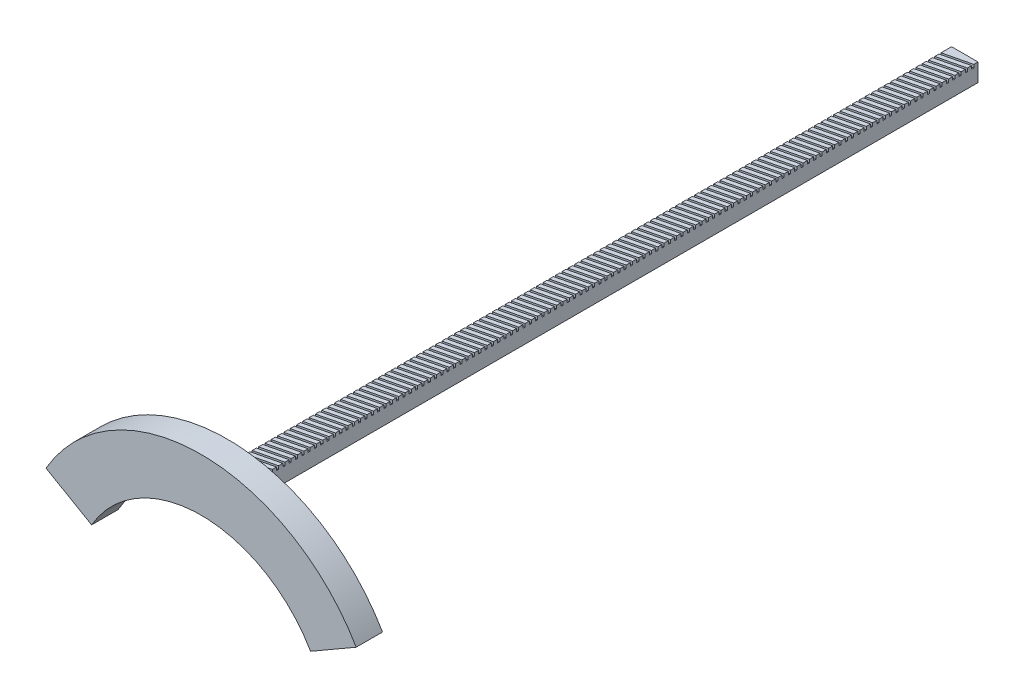
SolidWorks part; units mm, degrees
ref_plane "Ön Düzlem" through (0, 0, 0) normal (0, 0, 1) x (1, 0, 0)
ref_plane "Üst Düzlem" through (0, 0, 0) normal (0, 1, 0) x (1, 0, 0)
ref_plane "Sağ Düzlem" through (0, 0, 0) normal (1, 0, 0) x (0, 0, -1)
sketch "Sketch1" plane through (0, 0, 0) normal (0, 0, 1) x (1, 0, 0)
  line L0 (0, 0) -> (-0.6272, 5.9671) construction
  line L1 (-0.6272, 5.9671) -> (0.6272, 5.9671) construction
  line L2 (0.6272, 5.9671) -> (0, 0) construction
  line L3 (-0.6272, 5.9671) -> (-0.6272, 6.9671)
  line L4 (-0.6272, 6.9671) -> (0.6272, 6.9671)
  line L5 (0.6272, 6.9671) -> (0.6272, 5.9671)
  circle A0 centre (0, 0) radius 6 construction
  arc A1 (-0.6272, 5.9671) -> (0.6272, 5.9671) centre (0, 0) cw
  dimension "D1" = 12
  dimension "D2" = 12
  dimension "D3" = 1
extrude "Boss-Extrude1" add sketch "Sketch1" along normal blind 35 contours L3 A1 L5 L4
sketch "Sketch2" plane through (0, 0, 35) normal (0, 0, 1) x (1, 0, 0)
  line L1 (0, 8.5) -> (0, 0) construction
  line L2 (0, 0) -> (-7.3612, 4.25) construction
  line L3 (-7.3612, 4.25) -> (-5.1962, 3)
  line L4 (0, 8.5) -> (0, 6)
  arc A0 (0, 8.5) -> (-7.3612, 4.25) centre (0, 0) ccw
  arc A1 (-5.1962, 3) -> (0, 6) centre (0, 0) cw
  dimension "D1" = 60
  dimension "D2" = 2.5
  dimension "D3" = 6
extrude "Boss-Extrude2" add sketch "Sketch2" along normal blind 1.25
mirror "Mirror1" about plane through (0, 8.5, 36.25) normal (-1, 0, 0) of "Boss-Extrude2"
sketch "Sketch3" plane through (0, 6.9671, 0) normal (0, 1, 0) x (1, 0, 0)
  line L0 (0.6272, -0.2) -> (-0.6272, -0.5)
  line L1 (0.6272, -35) -> (0.6272, 0) construction
  line L2 (-0.6272, -35) -> (-0.6272, 0) construction
  line L3 (-0.6272, -0.5) -> (-0.6272, -0.6)
  line L4 (-0.6272, -0.6) -> (0.6272, -0.3)
  line L5 (0.6272, -0.3) -> (0.6272, -0.2)
  line L278 (-0.6272, -0.8) -> (-0.6272, -0.9)
  line L279 (-0.6272, -0.9) -> (0.6272, -0.6)
  line L280 (0.6272, -0.5) -> (-0.6272, -0.8)
  line L281 (0.6272, -0.6) -> (0.6272, -0.5)
  line L282 (-0.6272, -1.1) -> (-0.6272, -1.2)
  line L283 (-0.6272, -1.2) -> (0.6272, -0.9)
  line L284 (0.6272, -0.8) -> (-0.6272, -1.1)
  line L285 (0.6272, -0.9) -> (0.6272, -0.8)
  line L286 (-0.6272, -1.4) -> (-0.6272, -1.5)
  line L287 (-0.6272, -1.5) -> (0.6272, -1.2)
  line L288 (0.6272, -1.1) -> (-0.6272, -1.4)
  line L289 (0.6272, -1.2) -> (0.6272, -1.1)
  line L290 (-0.6272, -1.7) -> (-0.6272, -1.8)
  line L291 (-0.6272, -1.8) -> (0.6272, -1.5)
  line L292 (0.6272, -1.4) -> (-0.6272, -1.7)
  line L293 (0.6272, -1.5) -> (0.6272, -1.4)
  line L294 (-0.6272, -1.9999) -> (-0.6272, -2.0999)
  line L295 (-0.6272, -2.0999) -> (0.6272, -1.7999)
  line L296 (0.6272, -1.6999) -> (-0.6272, -1.9999)
  line L297 (0.6272, -1.7999) -> (0.6272, -1.6999)
  line L298 (-0.6272, -2.2999) -> (-0.6272, -2.3999)
  line L299 (-0.6272, -2.3999) -> (0.6272, -2.0999)
  line L300 (0.6272, -1.9999) -> (-0.6272, -2.2999)
  line L301 (0.6272, -2.0999) -> (0.6272, -1.9999)
  line L302 (-0.6272, -2.5999) -> (-0.6272, -2.6999)
  line L303 (-0.6272, -2.6999) -> (0.6272, -2.3999)
  line L304 (0.6272, -2.2999) -> (-0.6272, -2.5999)
  line L305 (0.6272, -2.3999) -> (0.6272, -2.2999)
  line L306 (-0.6272, -2.8999) -> (-0.6272, -2.9999)
  line L307 (-0.6272, -2.9999) -> (0.6272, -2.6999)
  line L308 (0.6272, -2.5999) -> (-0.6272, -2.8999)
  line L309 (0.6272, -2.6999) -> (0.6272, -2.5999)
  line L310 (-0.6272, -3.1999) -> (-0.6272, -3.2999)
  line L311 (-0.6272, -3.2999) -> (0.6272, -2.9999)
  line L312 (0.6272, -2.8999) -> (-0.6272, -3.1999)
  line L313 (0.6272, -2.9999) -> (0.6272, -2.8999)
  line L314 (-0.6272, -3.4999) -> (-0.6272, -3.5999)
  line L315 (-0.6272, -3.5999) -> (0.6272, -3.2999)
  line L316 (0.6272, -3.1999) -> (-0.6272, -3.4999)
  line L317 (0.6272, -3.2999) -> (0.6272, -3.1999)
  line L318 (-0.6272, -3.7999) -> (-0.6272, -3.8999)
  line L319 (-0.6272, -3.8999) -> (0.6272, -3.5999)
  line L320 (0.6272, -3.4999) -> (-0.6272, -3.7999)
  line L321 (0.6272, -3.5999) -> (0.6272, -3.4999)
  line L322 (-0.6272, -4.0999) -> (-0.6272, -4.1999)
  line L323 (-0.6272, -4.1999) -> (0.6272, -3.8999)
  line L324 (0.6272, -3.7999) -> (-0.6272, -4.0999)
  line L325 (0.6272, -3.8999) -> (0.6272, -3.7999)
  line L326 (-0.6272, -4.3999) -> (-0.6272, -4.4999)
  line L327 (-0.6272, -4.4999) -> (0.6272, -4.1999)
  line L328 (0.6272, -4.0999) -> (-0.6272, -4.3999)
  line L329 (0.6272, -4.1999) -> (0.6272, -4.0999)
  line L330 (-0.6272, -4.6999) -> (-0.6272, -4.7999)
  line L331 (-0.6272, -4.7999) -> (0.6272, -4.4999)
  line L332 (0.6272, -4.3999) -> (-0.6272, -4.6999)
  line L333 (0.6272, -4.4999) -> (0.6272, -4.3999)
  line L334 (-0.6272, -4.9998) -> (-0.6272, -5.0998)
  line L335 (-0.6272, -5.0998) -> (0.6272, -4.7998)
  line L336 (0.6272, -4.6998) -> (-0.6272, -4.9998)
  line L337 (0.6272, -4.7998) -> (0.6272, -4.6998)
  line L338 (-0.6272, -5.2998) -> (-0.6272, -5.3998)
  line L339 (-0.6272, -5.3998) -> (0.6272, -5.0998)
  line L340 (0.6272, -4.9998) -> (-0.6272, -5.2998)
  line L341 (0.6272, -5.0998) -> (0.6272, -4.9998)
  line L342 (-0.6272, -5.5998) -> (-0.6272, -5.6998)
  line L343 (-0.6272, -5.6998) -> (0.6272, -5.3998)
  line L344 (0.6272, -5.2998) -> (-0.6272, -5.5998)
  line L345 (0.6272, -5.3998) -> (0.6272, -5.2998)
  line L346 (-0.6272, -5.8998) -> (-0.6272, -5.9998)
  line L347 (-0.6272, -5.9998) -> (0.6272, -5.6998)
  line L348 (0.6272, -5.5998) -> (-0.6272, -5.8998)
  line L349 (0.6272, -5.6998) -> (0.6272, -5.5998)
  line L350 (-0.6272, -6.1998) -> (-0.6272, -6.2998)
  line L351 (-0.6272, -6.2998) -> (0.6272, -5.9998)
  line L352 (0.6272, -5.8998) -> (-0.6272, -6.1998)
  line L353 (0.6272, -5.9998) -> (0.6272, -5.8998)
  line L354 (-0.6272, -6.4998) -> (-0.6272, -6.5998)
  line L355 (-0.6272, -6.5998) -> (0.6272, -6.2998)
  line L356 (0.6272, -6.1998) -> (-0.6272, -6.4998)
  line L357 (0.6272, -6.2998) -> (0.6272, -6.1998)
  line L358 (-0.6272, -6.7998) -> (-0.6272, -6.8998)
  line L359 (-0.6272, -6.8998) -> (0.6272, -6.5998)
  line L360 (0.6272, -6.4998) -> (-0.6272, -6.7998)
  line L361 (0.6272, -6.5998) -> (0.6272, -6.4998)
  line L362 (-0.6272, -7.0998) -> (-0.6272, -7.1998)
  line L363 (-0.6272, -7.1998) -> (0.6272, -6.8998)
  line L364 (0.6272, -6.7998) -> (-0.6272, -7.0998)
  line L365 (0.6272, -6.8998) -> (0.6272, -6.7998)
  line L366 (-0.6272, -7.3998) -> (-0.6272, -7.4998)
  line L367 (-0.6272, -7.4998) -> (0.6272, -7.1998)
  line L368 (0.6272, -7.0998) -> (-0.6272, -7.3998)
  line L369 (0.6272, -7.1998) -> (0.6272, -7.0998)
  line L370 (-0.6272, -7.6998) -> (-0.6272, -7.7998)
  line L371 (-0.6272, -7.7998) -> (0.6272, -7.4998)
  line L372 (0.6272, -7.3998) -> (-0.6272, -7.6998)
  line L373 (0.6272, -7.4998) -> (0.6272, -7.3998)
  line L374 (-0.6272, -7.9997) -> (-0.6272, -8.0997)
  line L375 (-0.6272, -8.0997) -> (0.6272, -7.7997)
  line L376 (0.6272, -7.6997) -> (-0.6272, -7.9997)
  line L377 (0.6272, -7.7997) -> (0.6272, -7.6997)
  line L378 (-0.6272, -8.2997) -> (-0.6272, -8.3997)
  line L379 (-0.6272, -8.3997) -> (0.6272, -8.0997)
  line L380 (0.6272, -7.9997) -> (-0.6272, -8.2997)
  line L381 (0.6272, -8.0997) -> (0.6272, -7.9997)
  line L382 (-0.6272, -8.5997) -> (-0.6272, -8.6997)
  line L383 (-0.6272, -8.6997) -> (0.6272, -8.3997)
  line L384 (0.6272, -8.2997) -> (-0.6272, -8.5997)
  line L385 (0.6272, -8.3997) -> (0.6272, -8.2997)
  line L386 (-0.6272, -8.8997) -> (-0.6272, -8.9997)
  line L387 (-0.6272, -8.9997) -> (0.6272, -8.6997)
  line L388 (0.6272, -8.5997) -> (-0.6272, -8.8997)
  line L389 (0.6272, -8.6997) -> (0.6272, -8.5997)
  line L390 (-0.6272, -9.1997) -> (-0.6272, -9.2997)
  line L391 (-0.6272, -9.2997) -> (0.6272, -8.9997)
  line L392 (0.6272, -8.8997) -> (-0.6272, -9.1997)
  line L393 (0.6272, -8.9997) -> (0.6272, -8.8997)
  line L394 (-0.6272, -9.4997) -> (-0.6272, -9.5997)
  line L395 (-0.6272, -9.5997) -> (0.6272, -9.2997)
  line L396 (0.6272, -9.1997) -> (-0.6272, -9.4997)
  line L397 (0.6272, -9.2997) -> (0.6272, -9.1997)
  line L398 (-0.6272, -9.7997) -> (-0.6272, -9.8997)
  line L399 (-0.6272, -9.8997) -> (0.6272, -9.5997)
  line L400 (0.6272, -9.4997) -> (-0.6272, -9.7997)
  line L401 (0.6272, -9.5997) -> (0.6272, -9.4997)
  line L402 (-0.6272, -10.0997) -> (-0.6272, -10.1997)
  line L403 (-0.6272, -10.1997) -> (0.6272, -9.8997)
  line L404 (0.6272, -9.7997) -> (-0.6272, -10.0997)
  line L405 (0.6272, -9.8997) -> (0.6272, -9.7997)
  line L406 (-0.6272, -10.3997) -> (-0.6272, -10.4997)
  line L407 (-0.6272, -10.4997) -> (0.6272, -10.1997)
  line L408 (0.6272, -10.0997) -> (-0.6272, -10.3997)
  line L409 (0.6272, -10.1997) -> (0.6272, -10.0997)
  line L410 (-0.6272, -10.6997) -> (-0.6272, -10.7997)
  line L411 (-0.6272, -10.7997) -> (0.6272, -10.4997)
  line L412 (0.6272, -10.3997) -> (-0.6272, -10.6997)
  line L413 (0.6272, -10.4997) -> (0.6272, -10.3997)
  line L414 (-0.6272, -10.9996) -> (-0.6272, -11.0996)
  line L415 (-0.6272, -11.0996) -> (0.6272, -10.7996)
  line L416 (0.6272, -10.6996) -> (-0.6272, -10.9996)
  line L417 (0.6272, -10.7996) -> (0.6272, -10.6996)
  line L418 (-0.6272, -11.2996) -> (-0.6272, -11.3996)
  line L419 (-0.6272, -11.3996) -> (0.6272, -11.0996)
  line L420 (0.6272, -10.9996) -> (-0.6272, -11.2996)
  line L421 (0.6272, -11.0996) -> (0.6272, -10.9996)
  line L422 (-0.6272, -11.5996) -> (-0.6272, -11.6996)
  line L423 (-0.6272, -11.6996) -> (0.6272, -11.3996)
  line L424 (0.6272, -11.2996) -> (-0.6272, -11.5996)
  line L425 (0.6272, -11.3996) -> (0.6272, -11.2996)
  line L426 (-0.6272, -11.8996) -> (-0.6272, -11.9996)
  line L427 (-0.6272, -11.9996) -> (0.6272, -11.6996)
  line L428 (0.6272, -11.5996) -> (-0.6272, -11.8996)
  line L429 (0.6272, -11.6996) -> (0.6272, -11.5996)
  line L430 (-0.6272, -12.1996) -> (-0.6272, -12.2996)
  line L431 (-0.6272, -12.2996) -> (0.6272, -11.9996)
  line L432 (0.6272, -11.8996) -> (-0.6272, -12.1996)
  line L433 (0.6272, -11.9996) -> (0.6272, -11.8996)
  line L434 (-0.6272, -12.4996) -> (-0.6272, -12.5996)
  line L435 (-0.6272, -12.5996) -> (0.6272, -12.2996)
  line L436 (0.6272, -12.1996) -> (-0.6272, -12.4996)
  line L437 (0.6272, -12.2996) -> (0.6272, -12.1996)
  line L438 (-0.6272, -12.7996) -> (-0.6272, -12.8996)
  line L439 (-0.6272, -12.8996) -> (0.6272, -12.5996)
  line L440 (0.6272, -12.4996) -> (-0.6272, -12.7996)
  line L441 (0.6272, -12.5996) -> (0.6272, -12.4996)
  line L442 (-0.6272, -13.0996) -> (-0.6272, -13.1996)
  line L443 (-0.6272, -13.1996) -> (0.6272, -12.8996)
  line L444 (0.6272, -12.7996) -> (-0.6272, -13.0996)
  line L445 (0.6272, -12.8996) -> (0.6272, -12.7996)
  line L446 (-0.6272, -13.3996) -> (-0.6272, -13.4996)
  line L447 (-0.6272, -13.4996) -> (0.6272, -13.1996)
  line L448 (0.6272, -13.0996) -> (-0.6272, -13.3996)
  line L449 (0.6272, -13.1996) -> (0.6272, -13.0996)
  line L450 (-0.6272, -13.6996) -> (-0.6272, -13.7996)
  line L451 (-0.6272, -13.7996) -> (0.6272, -13.4996)
  line L452 (0.6272, -13.3996) -> (-0.6272, -13.6996)
  line L453 (0.6272, -13.4996) -> (0.6272, -13.3996)
  line L454 (-0.6272, -13.9995) -> (-0.6272, -14.0995)
  line L455 (-0.6272, -14.0995) -> (0.6272, -13.7995)
  line L456 (0.6272, -13.6995) -> (-0.6272, -13.9995)
  line L457 (0.6272, -13.7995) -> (0.6272, -13.6995)
  line L458 (-0.6272, -14.2995) -> (-0.6272, -14.3995)
  line L459 (-0.6272, -14.3995) -> (0.6272, -14.0995)
  line L460 (0.6272, -13.9995) -> (-0.6272, -14.2995)
  line L461 (0.6272, -14.0995) -> (0.6272, -13.9995)
  line L462 (-0.6272, -14.5995) -> (-0.6272, -14.6995)
  line L463 (-0.6272, -14.6995) -> (0.6272, -14.3995)
  line L464 (0.6272, -14.2995) -> (-0.6272, -14.5995)
  line L465 (0.6272, -14.3995) -> (0.6272, -14.2995)
  line L466 (-0.6272, -14.8995) -> (-0.6272, -14.9995)
  line L467 (-0.6272, -14.9995) -> (0.6272, -14.6995)
  line L468 (0.6272, -14.5995) -> (-0.6272, -14.8995)
  line L469 (0.6272, -14.6995) -> (0.6272, -14.5995)
  line L470 (-0.6272, -15.1995) -> (-0.6272, -15.2995)
  line L471 (-0.6272, -15.2995) -> (0.6272, -14.9995)
  line L472 (0.6272, -14.8995) -> (-0.6272, -15.1995)
  line L473 (0.6272, -14.9995) -> (0.6272, -14.8995)
  line L474 (-0.6272, -15.4995) -> (-0.6272, -15.5995)
  line L475 (-0.6272, -15.5995) -> (0.6272, -15.2995)
  line L476 (0.6272, -15.1995) -> (-0.6272, -15.4995)
  line L477 (0.6272, -15.2995) -> (0.6272, -15.1995)
  line L478 (-0.6272, -15.7995) -> (-0.6272, -15.8995)
  line L479 (-0.6272, -15.8995) -> (0.6272, -15.5995)
  line L480 (0.6272, -15.4995) -> (-0.6272, -15.7995)
  line L481 (0.6272, -15.5995) -> (0.6272, -15.4995)
  line L482 (-0.6272, -16.0995) -> (-0.6272, -16.1995)
  line L483 (-0.6272, -16.1995) -> (0.6272, -15.8995)
  line L484 (0.6272, -15.7995) -> (-0.6272, -16.0995)
  line L485 (0.6272, -15.8995) -> (0.6272, -15.7995)
  line L486 (-0.6272, -16.3995) -> (-0.6272, -16.4995)
  line L487 (-0.6272, -16.4995) -> (0.6272, -16.1995)
  line L488 (0.6272, -16.0995) -> (-0.6272, -16.3995)
  line L489 (0.6272, -16.1995) -> (0.6272, -16.0995)
  line L490 (-0.6272, -16.6995) -> (-0.6272, -16.7995)
  line L491 (-0.6272, -16.7995) -> (0.6272, -16.4995)
  line L492 (0.6272, -16.3995) -> (-0.6272, -16.6995)
  line L493 (0.6272, -16.4995) -> (0.6272, -16.3995)
  line L494 (-0.6272, -16.9994) -> (-0.6272, -17.0994)
  line L495 (-0.6272, -17.0994) -> (0.6272, -16.7994)
  line L496 (0.6272, -16.6994) -> (-0.6272, -16.9994)
  line L497 (0.6272, -16.7994) -> (0.6272, -16.6994)
  line L498 (-0.6272, -17.2994) -> (-0.6272, -17.3994)
  line L499 (-0.6272, -17.3994) -> (0.6272, -17.0994)
  line L500 (0.6272, -16.9994) -> (-0.6272, -17.2994)
  line L501 (0.6272, -17.0994) -> (0.6272, -16.9994)
  line L502 (-0.6272, -17.5994) -> (-0.6272, -17.6994)
  line L503 (-0.6272, -17.6994) -> (0.6272, -17.3994)
  line L504 (0.6272, -17.2994) -> (-0.6272, -17.5994)
  line L505 (0.6272, -17.3994) -> (0.6272, -17.2994)
  line L506 (-0.6272, -17.8994) -> (-0.6272, -17.9994)
  line L507 (-0.6272, -17.9994) -> (0.6272, -17.6994)
  line L508 (0.6272, -17.5994) -> (-0.6272, -17.8994)
  line L509 (0.6272, -17.6994) -> (0.6272, -17.5994)
  line L510 (-0.6272, -18.1994) -> (-0.6272, -18.2994)
  line L511 (-0.6272, -18.2994) -> (0.6272, -17.9994)
  line L512 (0.6272, -17.8994) -> (-0.6272, -18.1994)
  line L513 (0.6272, -17.9994) -> (0.6272, -17.8994)
  line L514 (-0.6272, -18.4994) -> (-0.6272, -18.5994)
  line L515 (-0.6272, -18.5994) -> (0.6272, -18.2994)
  line L516 (0.6272, -18.1994) -> (-0.6272, -18.4994)
  line L517 (0.6272, -18.2994) -> (0.6272, -18.1994)
  line L518 (-0.6272, -18.7994) -> (-0.6272, -18.8994)
  line L519 (-0.6272, -18.8994) -> (0.6272, -18.5994)
  line L520 (0.6272, -18.4994) -> (-0.6272, -18.7994)
  line L521 (0.6272, -18.5994) -> (0.6272, -18.4994)
  line L522 (-0.6272, -19.0994) -> (-0.6272, -19.1994)
  line L523 (-0.6272, -19.1994) -> (0.6272, -18.8994)
  line L524 (0.6272, -18.7994) -> (-0.6272, -19.0994)
  line L525 (0.6272, -18.8994) -> (0.6272, -18.7994)
  line L526 (-0.6272, -19.3994) -> (-0.6272, -19.4994)
  line L527 (-0.6272, -19.4994) -> (0.6272, -19.1994)
  line L528 (0.6272, -19.0994) -> (-0.6272, -19.3994)
  line L529 (0.6272, -19.1994) -> (0.6272, -19.0994)
  line L530 (-0.6272, -19.6993) -> (-0.6272, -19.7993)
  line L531 (-0.6272, -19.7993) -> (0.6272, -19.4993)
  line L532 (0.6272, -19.3993) -> (-0.6272, -19.6993)
  line L533 (0.6272, -19.4993) -> (0.6272, -19.3993)
  line L534 (-0.6272, -19.9993) -> (-0.6272, -20.0993)
  line L535 (-0.6272, -20.0993) -> (0.6272, -19.7993)
  line L536 (0.6272, -19.6993) -> (-0.6272, -19.9993)
  line L537 (0.6272, -19.7993) -> (0.6272, -19.6993)
  line L538 (-0.6272, -20.2993) -> (-0.6272, -20.3993)
  line L539 (-0.6272, -20.3993) -> (0.6272, -20.0993)
  line L540 (0.6272, -19.9993) -> (-0.6272, -20.2993)
  line L541 (0.6272, -20.0993) -> (0.6272, -19.9993)
  line L542 (-0.6272, -20.5993) -> (-0.6272, -20.6993)
  line L543 (-0.6272, -20.6993) -> (0.6272, -20.3993)
  line L544 (0.6272, -20.2993) -> (-0.6272, -20.5993)
  line L545 (0.6272, -20.3993) -> (0.6272, -20.2993)
  line L546 (-0.6272, -20.8993) -> (-0.6272, -20.9993)
  line L547 (-0.6272, -20.9993) -> (0.6272, -20.6993)
  line L548 (0.6272, -20.5993) -> (-0.6272, -20.8993)
  line L549 (0.6272, -20.6993) -> (0.6272, -20.5993)
  line L550 (-0.6272, -21.1993) -> (-0.6272, -21.2993)
  line L551 (-0.6272, -21.2993) -> (0.6272, -20.9993)
  line L552 (0.6272, -20.8993) -> (-0.6272, -21.1993)
  line L553 (0.6272, -20.9993) -> (0.6272, -20.8993)
  line L554 (-0.6272, -21.4993) -> (-0.6272, -21.5993)
  line L555 (-0.6272, -21.5993) -> (0.6272, -21.2993)
  line L556 (0.6272, -21.1993) -> (-0.6272, -21.4993)
  line L557 (0.6272, -21.2993) -> (0.6272, -21.1993)
  line L558 (-0.6272, -21.7993) -> (-0.6272, -21.8993)
  line L559 (-0.6272, -21.8993) -> (0.6272, -21.5993)
  line L560 (0.6272, -21.4993) -> (-0.6272, -21.7993)
  line L561 (0.6272, -21.5993) -> (0.6272, -21.4993)
  line L562 (-0.6272, -22.0993) -> (-0.6272, -22.1993)
  line L563 (-0.6272, -22.1993) -> (0.6272, -21.8993)
  line L564 (0.6272, -21.7993) -> (-0.6272, -22.0993)
  line L565 (0.6272, -21.8993) -> (0.6272, -21.7993)
  line L566 (-0.6272, -22.3993) -> (-0.6272, -22.4993)
  line L567 (-0.6272, -22.4993) -> (0.6272, -22.1993)
  line L568 (0.6272, -22.0993) -> (-0.6272, -22.3993)
  line L569 (0.6272, -22.1993) -> (0.6272, -22.0993)
  line L570 (-0.6272, -22.6992) -> (-0.6272, -22.7992)
  line L571 (-0.6272, -22.7992) -> (0.6272, -22.4992)
  line L572 (0.6272, -22.3992) -> (-0.6272, -22.6992)
  line L573 (0.6272, -22.4992) -> (0.6272, -22.3992)
  line L574 (-0.6272, -22.9992) -> (-0.6272, -23.0992)
  line L575 (-0.6272, -23.0992) -> (0.6272, -22.7992)
  line L576 (0.6272, -22.6992) -> (-0.6272, -22.9992)
  line L577 (0.6272, -22.7992) -> (0.6272, -22.6992)
  line L578 (-0.6272, -23.2992) -> (-0.6272, -23.3992)
  line L579 (-0.6272, -23.3992) -> (0.6272, -23.0992)
  line L580 (0.6272, -22.9992) -> (-0.6272, -23.2992)
  line L581 (0.6272, -23.0992) -> (0.6272, -22.9992)
  line L582 (-0.6272, -23.5992) -> (-0.6272, -23.6992)
  line L583 (-0.6272, -23.6992) -> (0.6272, -23.3992)
  line L584 (0.6272, -23.2992) -> (-0.6272, -23.5992)
  line L585 (0.6272, -23.3992) -> (0.6272, -23.2992)
  line L586 (-0.6272, -23.8992) -> (-0.6272, -23.9992)
  line L587 (-0.6272, -23.9992) -> (0.6272, -23.6992)
  line L588 (0.6272, -23.5992) -> (-0.6272, -23.8992)
  line L589 (0.6272, -23.6992) -> (0.6272, -23.5992)
  line L590 (-0.6272, -24.1992) -> (-0.6272, -24.2992)
  line L591 (-0.6272, -24.2992) -> (0.6272, -23.9992)
  line L592 (0.6272, -23.8992) -> (-0.6272, -24.1992)
  line L593 (0.6272, -23.9992) -> (0.6272, -23.8992)
  line L594 (-0.6272, -24.4992) -> (-0.6272, -24.5992)
  line L595 (-0.6272, -24.5992) -> (0.6272, -24.2992)
  line L596 (0.6272, -24.1992) -> (-0.6272, -24.4992)
  line L597 (0.6272, -24.2992) -> (0.6272, -24.1992)
  line L598 (-0.6272, -24.7992) -> (-0.6272, -24.8992)
  line L599 (-0.6272, -24.8992) -> (0.6272, -24.5992)
  line L600 (0.6272, -24.4992) -> (-0.6272, -24.7992)
  line L601 (0.6272, -24.5992) -> (0.6272, -24.4992)
  line L602 (-0.6272, -25.0992) -> (-0.6272, -25.1992)
  line L603 (-0.6272, -25.1992) -> (0.6272, -24.8992)
  line L604 (0.6272, -24.7992) -> (-0.6272, -25.0992)
  line L605 (0.6272, -24.8992) -> (0.6272, -24.7992)
  line L606 (-0.6272, -25.3992) -> (-0.6272, -25.4992)
  line L607 (-0.6272, -25.4992) -> (0.6272, -25.1992)
  line L608 (0.6272, -25.0992) -> (-0.6272, -25.3992)
  line L609 (0.6272, -25.1992) -> (0.6272, -25.0992)
  line L610 (-0.6272, -25.6991) -> (-0.6272, -25.7991)
  line L611 (-0.6272, -25.7991) -> (0.6272, -25.4991)
  line L612 (0.6272, -25.3991) -> (-0.6272, -25.6991)
  line L613 (0.6272, -25.4991) -> (0.6272, -25.3991)
  line L614 (-0.6272, -25.9991) -> (-0.6272, -26.0991)
  line L615 (-0.6272, -26.0991) -> (0.6272, -25.7991)
  line L616 (0.6272, -25.6991) -> (-0.6272, -25.9991)
  line L617 (0.6272, -25.7991) -> (0.6272, -25.6991)
  line L618 (-0.6272, -26.2991) -> (-0.6272, -26.3991)
  line L619 (-0.6272, -26.3991) -> (0.6272, -26.0991)
  line L620 (0.6272, -25.9991) -> (-0.6272, -26.2991)
  line L621 (0.6272, -26.0991) -> (0.6272, -25.9991)
  line L622 (-0.6272, -26.5991) -> (-0.6272, -26.6991)
  line L623 (-0.6272, -26.6991) -> (0.6272, -26.3991)
  line L624 (0.6272, -26.2991) -> (-0.6272, -26.5991)
  line L625 (0.6272, -26.3991) -> (0.6272, -26.2991)
  line L626 (-0.6272, -26.8991) -> (-0.6272, -26.9991)
  line L627 (-0.6272, -26.9991) -> (0.6272, -26.6991)
  line L628 (0.6272, -26.5991) -> (-0.6272, -26.8991)
  line L629 (0.6272, -26.6991) -> (0.6272, -26.5991)
  line L630 (-0.6272, -27.1991) -> (-0.6272, -27.2991)
  line L631 (-0.6272, -27.2991) -> (0.6272, -26.9991)
  line L632 (0.6272, -26.8991) -> (-0.6272, -27.1991)
  line L633 (0.6272, -26.9991) -> (0.6272, -26.8991)
  line L634 (-0.6272, -27.4991) -> (-0.6272, -27.5991)
  line L635 (-0.6272, -27.5991) -> (0.6272, -27.2991)
  line L636 (0.6272, -27.1991) -> (-0.6272, -27.4991)
  line L637 (0.6272, -27.2991) -> (0.6272, -27.1991)
  line L638 (-0.6272, -27.7991) -> (-0.6272, -27.8991)
  line L639 (-0.6272, -27.8991) -> (0.6272, -27.5991)
  line L640 (0.6272, -27.4991) -> (-0.6272, -27.7991)
  line L641 (0.6272, -27.5991) -> (0.6272, -27.4991)
  line L642 (-0.6272, -28.0991) -> (-0.6272, -28.1991)
  line L643 (-0.6272, -28.1991) -> (0.6272, -27.8991)
  line L644 (0.6272, -27.7991) -> (-0.6272, -28.0991)
  line L645 (0.6272, -27.8991) -> (0.6272, -27.7991)
  line L646 (-0.6272, -28.3991) -> (-0.6272, -28.4991)
  line L647 (-0.6272, -28.4991) -> (0.6272, -28.1991)
  line L648 (0.6272, -28.0991) -> (-0.6272, -28.3991)
  line L649 (0.6272, -28.1991) -> (0.6272, -28.0991)
  line L650 (-0.6272, -28.699) -> (-0.6272, -28.799)
  line L651 (-0.6272, -28.799) -> (0.6272, -28.499)
  line L652 (0.6272, -28.399) -> (-0.6272, -28.699)
  line L653 (0.6272, -28.499) -> (0.6272, -28.399)
  line L654 (-0.6272, -28.999) -> (-0.6272, -29.099)
  line L655 (-0.6272, -29.099) -> (0.6272, -28.799)
  line L656 (0.6272, -28.699) -> (-0.6272, -28.999)
  line L657 (0.6272, -28.799) -> (0.6272, -28.699)
  line L658 (-0.6272, -29.299) -> (-0.6272, -29.399)
  line L659 (-0.6272, -29.399) -> (0.6272, -29.099)
  line L660 (0.6272, -28.999) -> (-0.6272, -29.299)
  line L661 (0.6272, -29.099) -> (0.6272, -28.999)
  line L662 (-0.6272, -29.599) -> (-0.6272, -29.699)
  line L663 (-0.6272, -29.699) -> (0.6272, -29.399)
  line L664 (0.6272, -29.299) -> (-0.6272, -29.599)
  line L665 (0.6272, -29.399) -> (0.6272, -29.299)
  line L666 (-0.6272, -29.899) -> (-0.6272, -29.999)
  line L667 (-0.6272, -29.999) -> (0.6272, -29.699)
  line L668 (0.6272, -29.599) -> (-0.6272, -29.899)
  line L669 (0.6272, -29.699) -> (0.6272, -29.599)
  line L670 (-0.6272, -30.199) -> (-0.6272, -30.299)
  line L671 (-0.6272, -30.299) -> (0.6272, -29.999)
  line L672 (0.6272, -29.899) -> (-0.6272, -30.199)
  line L673 (0.6272, -29.999) -> (0.6272, -29.899)
  line L674 (-0.6272, -30.499) -> (-0.6272, -30.599)
  line L675 (-0.6272, -30.599) -> (0.6272, -30.299)
  line L676 (0.6272, -30.199) -> (-0.6272, -30.499)
  line L677 (0.6272, -30.299) -> (0.6272, -30.199)
  line L678 (-0.6272, -30.799) -> (-0.6272, -30.899)
  line L679 (-0.6272, -30.899) -> (0.6272, -30.599)
  line L680 (0.6272, -30.499) -> (-0.6272, -30.799)
  line L681 (0.6272, -30.599) -> (0.6272, -30.499)
  line L682 (-0.6272, -31.099) -> (-0.6272, -31.199)
  line L683 (-0.6272, -31.199) -> (0.6272, -30.899)
  line L684 (0.6272, -30.799) -> (-0.6272, -31.099)
  line L685 (0.6272, -30.899) -> (0.6272, -30.799)
  line L686 (-0.6272, -31.399) -> (-0.6272, -31.499)
  line L687 (-0.6272, -31.499) -> (0.6272, -31.199)
  line L688 (0.6272, -31.099) -> (-0.6272, -31.399)
  line L689 (0.6272, -31.199) -> (0.6272, -31.099)
  line L690 (-0.6272, -31.6989) -> (-0.6272, -31.7989)
  line L691 (-0.6272, -31.7989) -> (0.6272, -31.4989)
  line L692 (0.6272, -31.3989) -> (-0.6272, -31.6989)
  line L693 (0.6272, -31.4989) -> (0.6272, -31.3989)
  line L694 (-0.6272, -31.9989) -> (-0.6272, -32.0989)
  line L695 (-0.6272, -32.0989) -> (0.6272, -31.7989)
  line L696 (0.6272, -31.6989) -> (-0.6272, -31.9989)
  line L697 (0.6272, -31.7989) -> (0.6272, -31.6989)
  line L698 (-0.6272, -32.2989) -> (-0.6272, -32.3989)
  line L699 (-0.6272, -32.3989) -> (0.6272, -32.0989)
  line L700 (0.6272, -31.9989) -> (-0.6272, -32.2989)
  line L701 (0.6272, -32.0989) -> (0.6272, -31.9989)
  line L702 (-0.6272, -32.5989) -> (-0.6272, -32.6989)
  line L703 (-0.6272, -32.6989) -> (0.6272, -32.3989)
  line L704 (0.6272, -32.2989) -> (-0.6272, -32.5989)
  line L705 (0.6272, -32.3989) -> (0.6272, -32.2989)
  line L706 (-0.6272, -32.8989) -> (-0.6272, -32.9989)
  line L707 (-0.6272, -32.9989) -> (0.6272, -32.6989)
  line L708 (0.6272, -32.5989) -> (-0.6272, -32.8989)
  line L709 (0.6272, -32.6989) -> (0.6272, -32.5989)
  line L710 (-0.6272, -33.1989) -> (-0.6272, -33.2989)
  line L711 (-0.6272, -33.2989) -> (0.6272, -32.9989)
  line L712 (0.6272, -32.8989) -> (-0.6272, -33.1989)
  line L713 (0.6272, -32.9989) -> (0.6272, -32.8989)
  line L714 (-0.6272, -33.4989) -> (-0.6272, -33.5989)
  line L715 (-0.6272, -33.5989) -> (0.6272, -33.2989)
  line L716 (0.6272, -33.1989) -> (-0.6272, -33.4989)
  line L717 (0.6272, -33.2989) -> (0.6272, -33.1989)
  line L718 (-0.6272, -33.7989) -> (-0.6272, -33.8989)
  line L719 (-0.6272, -33.8989) -> (0.6272, -33.5989)
  line L720 (0.6272, -33.4989) -> (-0.6272, -33.7989)
  line L721 (0.6272, -33.5989) -> (0.6272, -33.4989)
  line L722 (-0.6272, -34.0989) -> (-0.6272, -34.1989)
  line L723 (-0.6272, -34.1989) -> (0.6272, -33.8989)
  line L724 (0.6272, -33.7989) -> (-0.6272, -34.0989)
  line L725 (0.6272, -33.8989) -> (0.6272, -33.7989)
  line L726 (-0.6272, -34.3988) -> (-0.6272, -34.4988)
  line L727 (-0.6272, -34.4988) -> (0.6272, -34.1988)
  line L728 (0.6272, -34.0988) -> (-0.6272, -34.3988)
  line L729 (0.6272, -34.1988) -> (0.6272, -34.0988)
  line L730 (-0.6272, -34.6988) -> (-0.6272, -34.7988)
  line L731 (-0.6272, -34.7988) -> (0.6272, -34.4988)
  line L732 (0.6272, -34.3988) -> (-0.6272, -34.6988)
  line L733 (0.6272, -34.4988) -> (0.6272, -34.3988)
  dimension "D1" = 0.1
  dimension "D2" = 0.2
  dimension "D3" = 0.5
  dimension "D4" = 115
extrude "Cut-Extrude1" cut sketch "Sketch3" against normal blind 0.3
sketch "Sketch4" plane through (0, 0, 0) normal (0, 0, -1) x (-1, 0, 0)
  line L0 (0.6272, 6.9671) -> (-0.6272, 6.9671) construction
  line L1 (-1.0212, 7.392) -> (0.9758, 7.392)
  line L2 (-1.0212, 7.392) -> (-1.0212, 6.8171)
  line L3 (-1.0212, 6.8171) -> (0.9758, 6.8171)
  line L4 (0.9758, 7.392) -> (0.9758, 6.8171)
  dimension "D1" = 0.15
extrude "Cut-Extrude2" cut sketch "Sketch4" against normal blind 35
